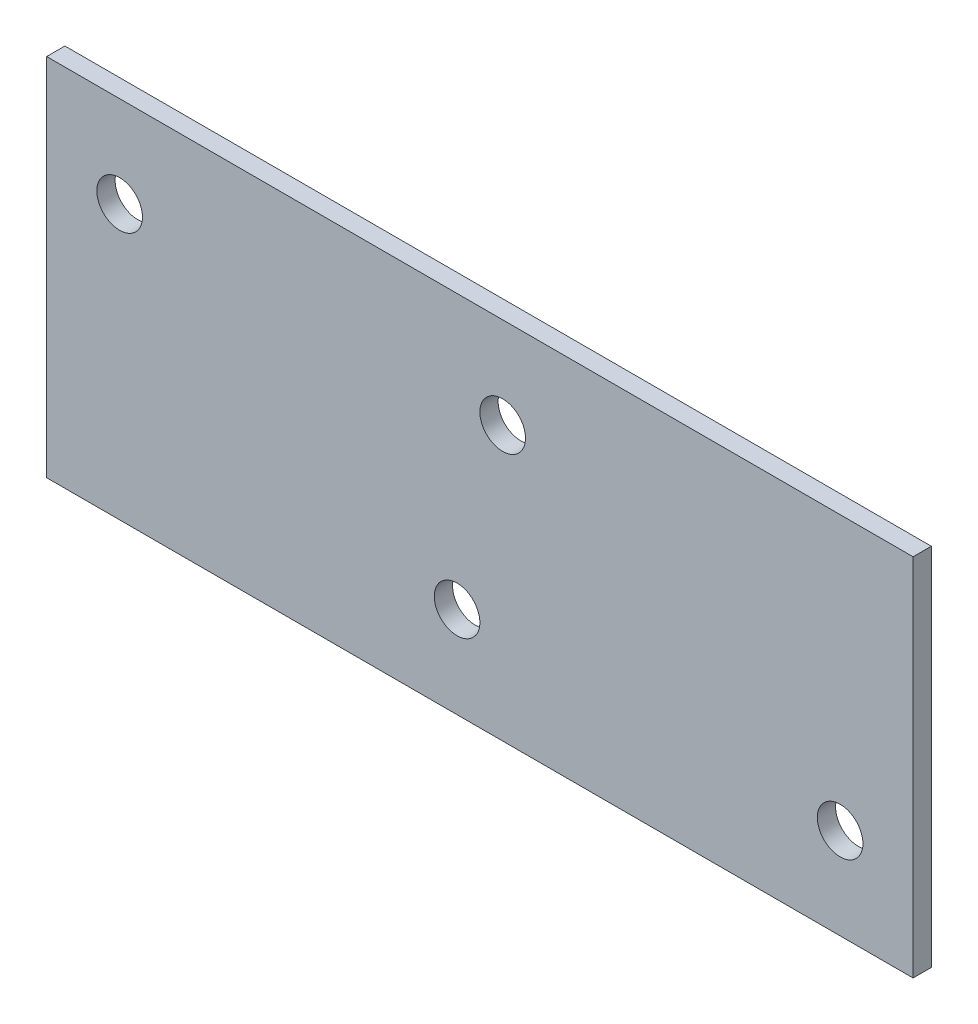
SolidWorks part; units mm, degrees
ref_plane "前视基准面" through (0, 0, 0) normal (0, 0, 1) x (1, 0, 0)
ref_plane "上视基准面" through (0, 0, 0) normal (0, 1, 0) x (1, 0, 0)
ref_plane "右视基准面" through (0, 0, 0) normal (1, 0, 0) x (0, 0, -1)
sketch "草图1" plane through (0, 0, 0) normal (0, 0, 1) x (1, 0, 0)
  line L0 (-37.5, 0) -> (57.5, 0) construction
  line L1 (57.5, 20) -> (-37.5, 20)
  line L2 (57.5, 20) -> (57.5, -20)
  line L3 (57.5, -20) -> (-37.5, -20)
  line L4 (-37.5, 20) -> (-37.5, -20)
  circle A0 centre (-29.5, 10) radius 2.5
  circle A1 centre (12.5, 10) radius 2.5
  circle A2 centre (7.5, -10) radius 2.5
  circle A3 centre (49.5, -10) radius 2.5
  point P0 (0, 0)
  point P21 (7.5, -10)
  point P22 (49.5, -10)
  dimension "D5" = 42
  dimension "D7" = 8
  dimension "D1" = 40
  dimension "D2" = 95
  dimension "D3" = 10
  dimension "D4" = 10
  dimension "D6" = 42
  dimension "D8" = 8
extrude "凸台-拉伸1" add sketch "草图1" along normal blind 2
